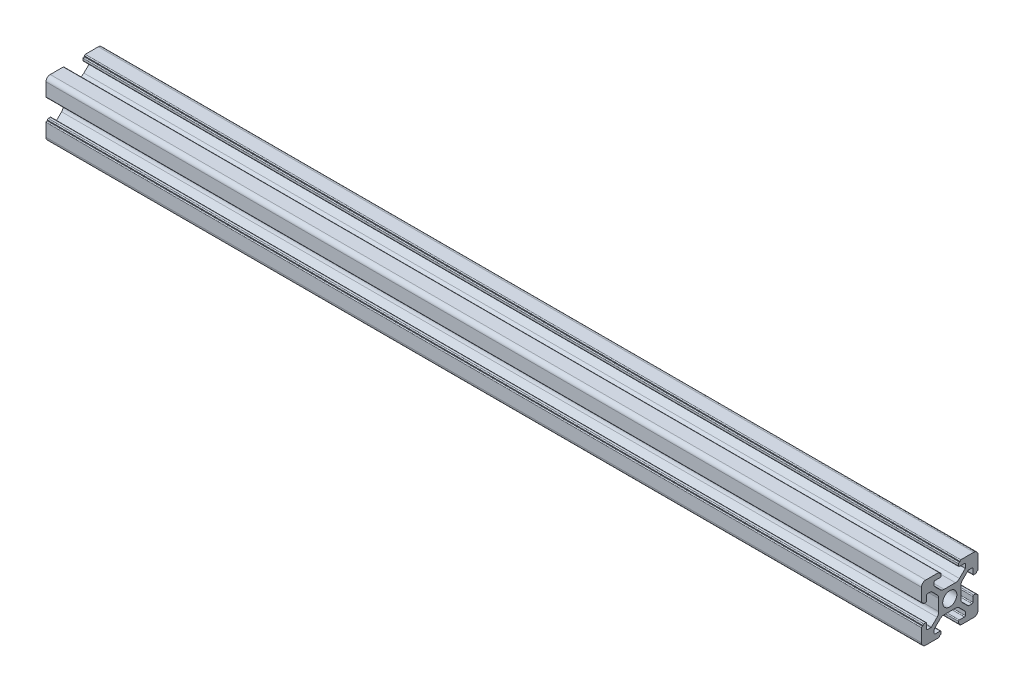
SolidWorks part; units mm, degrees
ref_plane "前视基准面" through (0, 0, 0) normal (0, 0, 1) x (1, 0, 0)
ref_plane "上视基准面" through (0, 0, 0) normal (0, 1, 0) x (1, 0, 0)
ref_plane "右视基准面" through (0, 0, 0) normal (1, 0, 0) x (0, 0, -1)
sketch "草图1" plane through (0, 0, 0) normal (0, 0, 1) x (1, 0, 0)
  line L0 (-129.1667, 49.1551) -> (180.8333, 49.1551)
  dimension "D1" = 310
other "铝型材 2020(1)"
ref_plane "基准面4" through (-129.1667, 49.1551, 0) normal (1, 0, 0) x (0, 1, 0)
sketch "草图11" plane through (-129.1667, 49.1551, 0) normal (1, 0, 0) x (0, 1, 0)
  line L0 (3.9, 0) -> (3.9, -2.0109)
  line L1 (4.4858, -3.4251) -> (6.5607, -5.5)
  line L2 (6.5607, -5.5) -> (7.9, -5.5)
  line L3 (8.2, -5.2) -> (8.2, -3.4)
  line L4 (8.5, -3.1) -> (9.2, -3.1)
  line L5 (9.5, -3.4) -> (9.5, -3.6)
  line L6 (9.5, -3.6) -> (9.7, -3.6)
  line L7 (10, -3.9) -> (10, -8.5)
  line L8 (8.5, -10) -> (3.9, -10)
  line L9 (3.1, -9.2) -> (3.1, -8.5)
  line L10 (3.4, -8.2) -> (5.2, -8.2)
  line L11 (5.5, -7.9) -> (5.5, -6.6849)
  line L12 (5.4121, -6.4728) -> (3.4251, -4.4858)
  line L13 (2.0109, -3.9) -> (0, -3.9)
  line L14 (0, -3.9) -> (-2.0109, -3.9)
  line L15 (-3.4251, -4.4858) -> (-5.4121, -6.4728)
  line L16 (-5.5, -6.6849) -> (-5.5, -7.9)
  line L17 (-5.2, -8.2) -> (-3.4, -8.2)
  line L18 (-3.1, -8.5) -> (-3.1, -9.2)
  line L19 (-3.9, -10) -> (-8.5, -10)
  line L20 (-10, -8.5) -> (-10, -3.9)
  line L21 (-9.7, -3.6) -> (-9.5, -3.6)
  line L22 (-9.5, -3.6) -> (-9.5, -3.4)
  line L23 (-9.2, -3.1) -> (-8.5, -3.1)
  line L24 (-8.2, -3.4) -> (-8.2, -5.2)
  line L25 (-7.9, -5.5) -> (-6.6849, -5.5)
  line L26 (-6.4728, -5.4121) -> (-4.4858, -3.4251)
  line L27 (-3.9, -2.0109) -> (-3.9, 0)
  line L28 (-3.9, 0) -> (-3.9, 2.0109)
  line L29 (-4.4858, 3.4251) -> (-6.4728, 5.4121)
  line L30 (-6.6849, 5.5) -> (-7.9, 5.5)
  line L31 (-8.2, 5.2) -> (-8.2, 3.4)
  line L32 (-8.5, 3.1) -> (-9.2, 3.1)
  line L33 (-9.5, 3.4) -> (-9.5, 3.6)
  line L34 (-9.5, 3.6) -> (-9.7, 3.6)
  line L35 (-10, 3.9) -> (-10, 8.5)
  line L36 (-8.5, 10) -> (-3.9, 10)
  line L37 (-3.6, 9.7) -> (-3.6, 9.5)
  line L38 (-3.6, 9.5) -> (-3.4, 9.5)
  line L39 (-3.1, 9.2) -> (-3.1, 8.5)
  line L40 (-3.4, 8.2) -> (-5.2, 8.2)
  line L41 (-5.5, 7.9) -> (-5.5, 6.6849)
  line L42 (-5.4121, 6.4728) -> (-3.4251, 4.4858)
  line L43 (-2.0109, 3.9) -> (0, 3.9)
  line L44 (0, 3.9) -> (2.0109, 3.9)
  line L45 (3.4251, 4.4858) -> (5.4121, 6.4728)
  line L46 (5.5, 6.6849) -> (5.5, 7.9)
  line L47 (5.2, 8.2) -> (3.4, 8.2)
  line L48 (3.1, 8.5) -> (3.1, 9.2)
  line L49 (3.4, 9.5) -> (3.6, 9.5)
  line L50 (3.6, 9.5) -> (3.6, 9.7)
  line L51 (3.9, 10) -> (8.5, 10)
  line L52 (10, 8.5) -> (10, 3.9)
  line L53 (9.7, 3.6) -> (9.5, 3.6)
  line L54 (9.5, 3.6) -> (9.5, 3.4)
  line L55 (9.2, 3.1) -> (8.5, 3.1)
  line L56 (8.2, 3.4) -> (8.2, 5.2)
  line L57 (7.9, 5.5) -> (6.6849, 5.5)
  line L58 (6.4728, 5.4121) -> (4.4858, 3.4251)
  line L59 (3.9, 2.0109) -> (3.9, 0)
  circle A0 centre (0, 0) radius 2.5
  arc A1 (3.9, -2.0109) -> (4.4858, -3.4251) centre (5.9, -2.0109) ccw
  arc A2 (7.9, -5.5) -> (8.2, -5.2) centre (7.9, -5.2) ccw
  arc A3 (8.5, -3.1) -> (8.2, -3.4) centre (8.5, -3.4) ccw
  arc A4 (9.5, -3.4) -> (9.2, -3.1) centre (9.2, -3.4) ccw
  arc A5 (10, -3.9) -> (9.7, -3.6) centre (9.7, -3.9) ccw
  arc A6 (8.5, -10) -> (10, -8.5) centre (8.5, -8.5) ccw
  arc A7 (3.6, -9.7) -> (3.9, -10) centre (3.9, -9.7) ccw
  arc A8 (3.6, -9.7) -> (3.4, -9.5) centre (3.4, -9.7) ccw
  arc A9 (3.1, -9.2) -> (3.4, -9.5) centre (3.4, -9.2) ccw
  arc A10 (3.4, -8.2) -> (3.1, -8.5) centre (3.4, -8.5) ccw
  arc A11 (5.2, -8.2) -> (5.5, -7.9) centre (5.2, -7.9) ccw
  arc A12 (5.5, -6.6849) -> (5.4121, -6.4728) centre (5.2, -6.6849) ccw
  arc A13 (3.4251, -4.4858) -> (2.0109, -3.9) centre (2.0109, -5.9) ccw
  arc A14 (-2.0109, -3.9) -> (-3.4251, -4.4858) centre (-2.0109, -5.9) ccw
  arc A15 (-5.4121, -6.4728) -> (-5.5, -6.6849) centre (-5.2, -6.6849) ccw
  arc A16 (-5.5, -7.9) -> (-5.2, -8.2) centre (-5.2, -7.9) ccw
  arc A17 (-3.1, -8.5) -> (-3.4, -8.2) centre (-3.4, -8.5) ccw
  arc A18 (-3.4, -9.5) -> (-3.1, -9.2) centre (-3.4, -9.2) ccw
  arc A19 (-3.4, -9.5) -> (-3.6, -9.7) centre (-3.4, -9.7) ccw
  arc A20 (-3.9, -10) -> (-3.6, -9.7) centre (-3.9, -9.7) ccw
  arc A21 (-10, -8.5) -> (-8.5, -10) centre (-8.5, -8.5) ccw
  arc A22 (-9.7, -3.6) -> (-10, -3.9) centre (-9.7, -3.9) ccw
  arc A23 (-9.2, -3.1) -> (-9.5, -3.4) centre (-9.2, -3.4) ccw
  arc A24 (-8.2, -3.4) -> (-8.5, -3.1) centre (-8.5, -3.4) ccw
  arc A25 (-8.2, -5.2) -> (-7.9, -5.5) centre (-7.9, -5.2) ccw
  arc A26 (-6.6849, -5.5) -> (-6.4728, -5.4121) centre (-6.6849, -5.2) ccw
  arc A27 (-4.4858, -3.4251) -> (-3.9, -2.0109) centre (-5.9, -2.0109) ccw
  arc A28 (-3.9, 2.0109) -> (-4.4858, 3.4251) centre (-5.9, 2.0109) ccw
  arc A29 (-6.4728, 5.4121) -> (-6.6849, 5.5) centre (-6.6849, 5.2) ccw
  arc A30 (-7.9, 5.5) -> (-8.2, 5.2) centre (-7.9, 5.2) ccw
  arc A31 (-8.5, 3.1) -> (-8.2, 3.4) centre (-8.5, 3.4) ccw
  arc A32 (-9.5, 3.4) -> (-9.2, 3.1) centre (-9.2, 3.4) ccw
  arc A33 (-10, 3.9) -> (-9.7, 3.6) centre (-9.7, 3.9) ccw
  arc A34 (-8.5, 10) -> (-10, 8.5) centre (-8.5, 8.5) ccw
  arc A35 (-3.6, 9.7) -> (-3.9, 10) centre (-3.9, 9.7) ccw
  arc A36 (-3.1, 9.2) -> (-3.4, 9.5) centre (-3.4, 9.2) ccw
  arc A37 (-3.4, 8.2) -> (-3.1, 8.5) centre (-3.4, 8.5) ccw
  arc A38 (-5.2, 8.2) -> (-5.5, 7.9) centre (-5.2, 7.9) ccw
  arc A39 (-5.5, 6.6849) -> (-5.4121, 6.4728) centre (-5.2, 6.6849) ccw
  arc A40 (-3.4251, 4.4858) -> (-2.0109, 3.9) centre (-2.0109, 5.9) ccw
  arc A41 (2.0109, 3.9) -> (3.4251, 4.4858) centre (2.0109, 5.9) ccw
  arc A42 (5.4121, 6.4728) -> (5.5, 6.6849) centre (5.2, 6.6849) ccw
  arc A43 (5.5, 7.9) -> (5.2, 8.2) centre (5.2, 7.9) ccw
  arc A44 (3.1, 8.5) -> (3.4, 8.2) centre (3.4, 8.5) ccw
  arc A45 (3.4, 9.5) -> (3.1, 9.2) centre (3.4, 9.2) ccw
  arc A46 (3.9, 10) -> (3.6, 9.7) centre (3.9, 9.7) ccw
  arc A47 (10, 8.5) -> (8.5, 10) centre (8.5, 8.5) ccw
  arc A48 (9.7, 3.6) -> (10, 3.9) centre (9.7, 3.9) ccw
  arc A49 (9.2, 3.1) -> (9.5, 3.4) centre (9.2, 3.4) ccw
  arc A50 (8.2, 3.4) -> (8.5, 3.1) centre (8.5, 3.4) ccw
  arc A51 (8.2, 5.2) -> (7.9, 5.5) centre (7.9, 5.2) ccw
  arc A52 (6.6849, 5.5) -> (6.4728, 5.4121) centre (6.6849, 5.2) ccw
  arc A53 (4.4858, 3.4251) -> (3.9, 2.0109) centre (5.9, 2.0109) ccw
  point P0 (0, 0)
